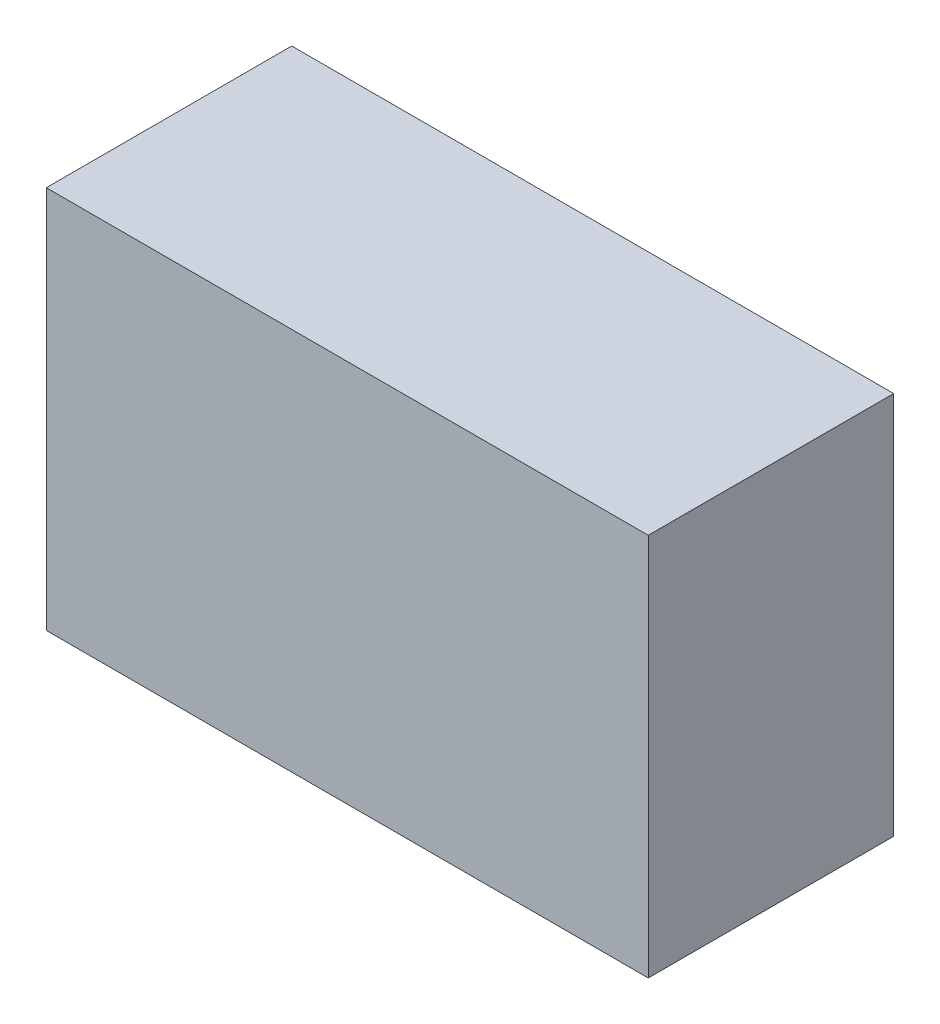
SolidWorks part; units mm, degrees
material "1060 Alloy"
ref_plane "Front" through (0, 0, 0) normal (0, 0, 1) x (1, 0, 0)
ref_plane "Top" through (0, 0, 0) normal (0, 1, 0) x (1, 0, 0)
ref_plane "Right" through (0, 0, 0) normal (1, 0, 0) x (0, 0, -1)
sketch "Sketch3" plane through (0, 0, 0) normal (0, 0, 1) x (1, 0, 0)
  line L0 (-0.127, -6.35) -> (30.1755, -6.35)
  line L1 (0, 0) -> (31.1484, 0)
  line L2 (0, 0) -> (0, -19.8376)
  line L3 (0, -19.8376) -> (31.1484, -19.8376)
  line L4 (31.1484, 0) -> (31.1484, -19.8376)
  line L5 (15.5742, -19.8376) -> (15.5742, 0) construction
  line L6 (15.5742, -6.35) -> (8.0621, -19.3614) construction
  line L15 (12.5496, -11.5887) -> (15.5742, -13.335) construction
  line L16 (15.5742, -6.35) -> (22.9274, -19.0862) construction
  circle A0 centre (15.5742, -6.35) radius 6.0492 construction
  point P14 (0, -6.35)
  point P17 (9.525, -6.35)
  point P19 (31.1484, -6.35)
  point P20 (7.7871, -19.8376)
  point P24 (23.3613, -19.8376)
  dimension "D2" = 6.35
  dimension "D6" = 3.4925
  dimension "D3" = 60
  dimension "D1" = 9.525
  dimension "D4" = 9.525
  dimension "D5" = 60
extrude "Boss-Extrude1" add sketch "Sketch3" along normal mid plane 12.7
sketch "Sketch4" plane through (0, 0, 0) normal (-1, 0, 0) x (0, 0, 1)
  circle A0 centre (0, -6.35) radius 3.175
  dimension "D1" = 6.35
extrude "Cut-Extrude1" cut sketch "Sketch4" against normal blind 9.525
ref_plane "Plane1" through (7.7871, -19.8376, 0) normal (-0.5, -0.866, 0) x (-0.866, 0.5, 0)
ref_plane "Mirror Plane" through (15.5742, 0, 0) normal (-1, 0, 0) x (0, 0, 1)
sketch "Sketch5" plane through (7.7871, -19.8376, 0) normal (-0.5, -0.866, 0) x (-0.866, 0.5, 0)
  circle A0 centre (0, 0) radius 3.175
  dimension "D1" = 6.35
extrude "Cut-Extrude5" cut sketch "Sketch5" against normal blind 9.525 and the other way up to next
sketch "Sketch6" plane through (0, 0, -6.35) normal (0, 0, -1) x (-1, 0, 0)
  circle A0 centre (-15.5742, -6.35) radius 3.175
  dimension "D1" = 6.35
extrude "Cut-Extrude6" cut sketch "Sketch6" against normal blind 9.525
mirror "Mirror1" about plane through (15.5742, 0, 0) normal (-1, 0, 0) of "Cut-Extrude5"
equation "\"truss_member_od\"= .25in"
equation "\"truss_member_id\"= 0in"
equation "\"truss_member_L1\"= 2.125in"
equation "\"connector_hole_depth\"= .375in"
equation "\"D1@Boss-Extrude1\"=\"truss_member_od\"*2"
equation "\"D6@Sketch3\"=\"truss_member_od\"/2*1.1"
equation "\"D1@Sketch4\"=\"truss_member_od\""
equation "\"D1@Cut-Extrude1\"=\"connector_hole_depth\""
equation "\"D1@Sketch3\"=\"connector_hole_depth\""
equation "\"D4@Sketch3\"=\"connector_hole_depth\""
equation "\"D1@Sketch5\"=\"truss_member_od\""
equation "\"D1@Cut-Extrude5\"=\"connector_hole_depth\""
equation "\"D1@Cut-Extrude6\"=\"connector_hole_depth\""
equation "\"D1@Sketch6\"=\"truss_member_od\""
